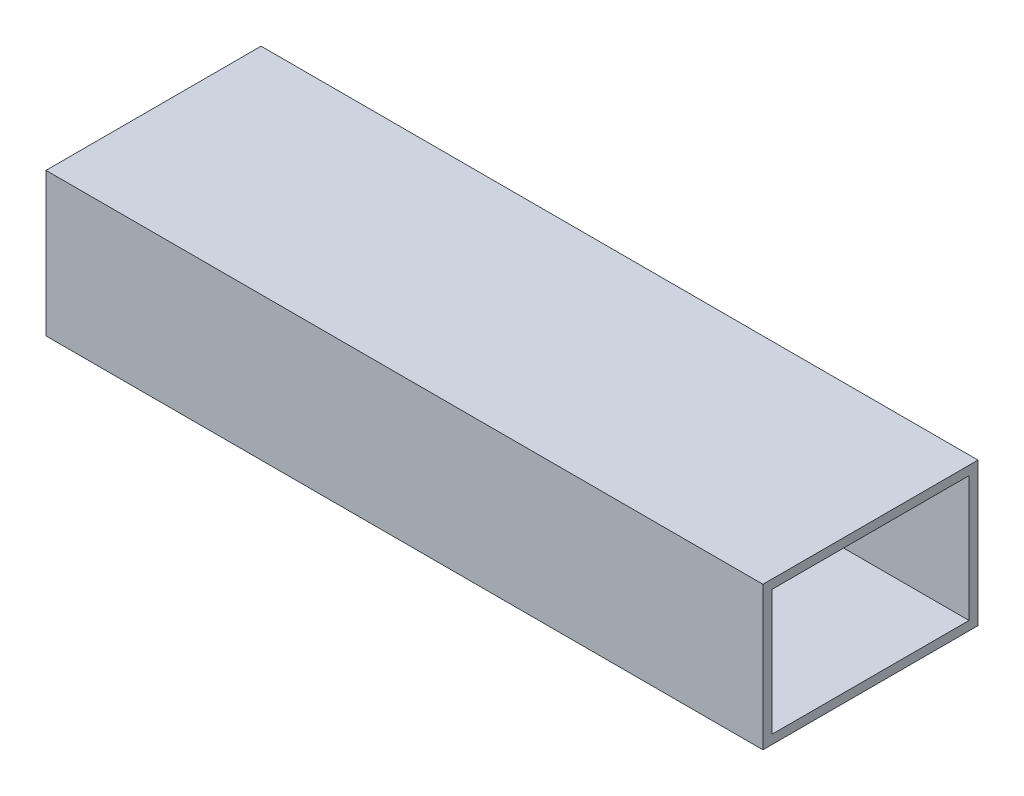
SolidWorks part; units mm, degrees
material "6061-T6 (SS)"
ref_plane "Front Plane" through (0, 0, 0) normal (0, 0, 1) x (1, 0, 0)
ref_plane "Top Plane" through (0, 0, 0) normal (0, 1, 0) x (1, 0, 0)
ref_plane "Right Plane" through (0, 0, 0) normal (1, 0, 0) x (0, 0, -1)
sketch "Sketch1" plane through (0, 0, 0) normal (1, 0, 0) x (0, 0, -1)
  line L0 (-34.925, 22.225) -> (34.925, 22.225)
  line L1 (-38.1, -25.4) -> (38.1, -25.4)
  line L2 (-38.1, -25.4) -> (-38.1, 25.4)
  line L3 (-38.1, 25.4) -> (38.1, 25.4)
  line L4 (38.1, -25.4) -> (38.1, 25.4)
  line L5 (-38.1, -25.4) -> (38.1, 25.4) construction
  line L6 (-38.1, 25.4) -> (38.1, -25.4) construction
  line L7 (34.925, -22.225) -> (34.925, 22.225)
  line L8 (-34.925, -22.225) -> (34.925, -22.225)
  line L9 (-34.925, -22.225) -> (-34.925, 22.225)
  point P0 (0, 0)
  dimension "D1" = 50.8
  dimension "D2" = 76.2
  dimension "D3" = 3.175
extrude "Boss-Extrude1" add sketch "Sketch1" along normal blind 254
